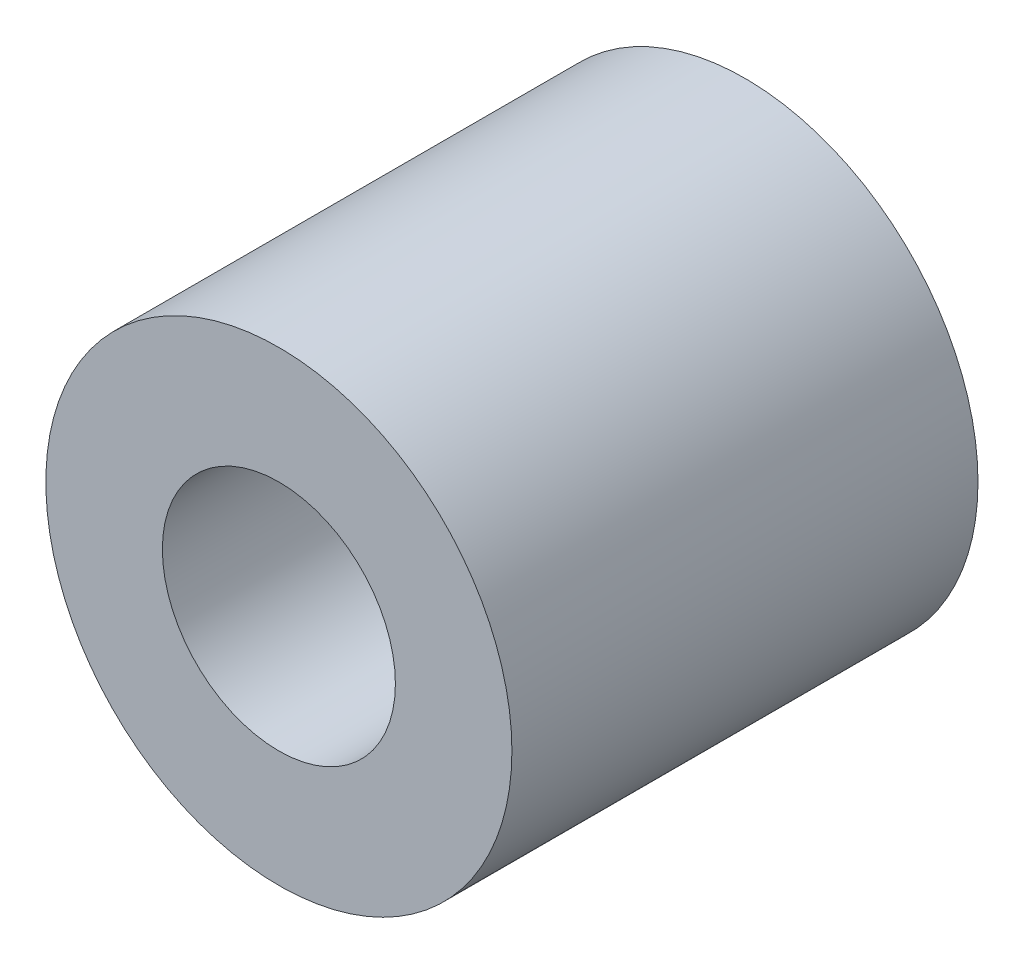
SolidWorks part; units mm, degrees
ref_plane "Спереди" through (0, 0, 0) normal (0, 0, 1) x (1, 0, 0)
ref_plane "Сверху" through (0, 0, 0) normal (0, 1, 0) x (1, 0, 0)
ref_plane "Справа" through (0, 0, 0) normal (1, 0, 0) x (0, 0, -1)
sketch "Эскиз1" plane through (0, 0, 0) normal (0, 0, 1) x (1, 0, 0)
  circle A0 centre (0, 0) radius 4
  circle A1 centre (0, 0) radius 2
  dimension "D1" = 8
  dimension "D2" = 4
extrude "Бобышка-Вытянуть1" add sketch "Эскиз1" along normal blind 8
